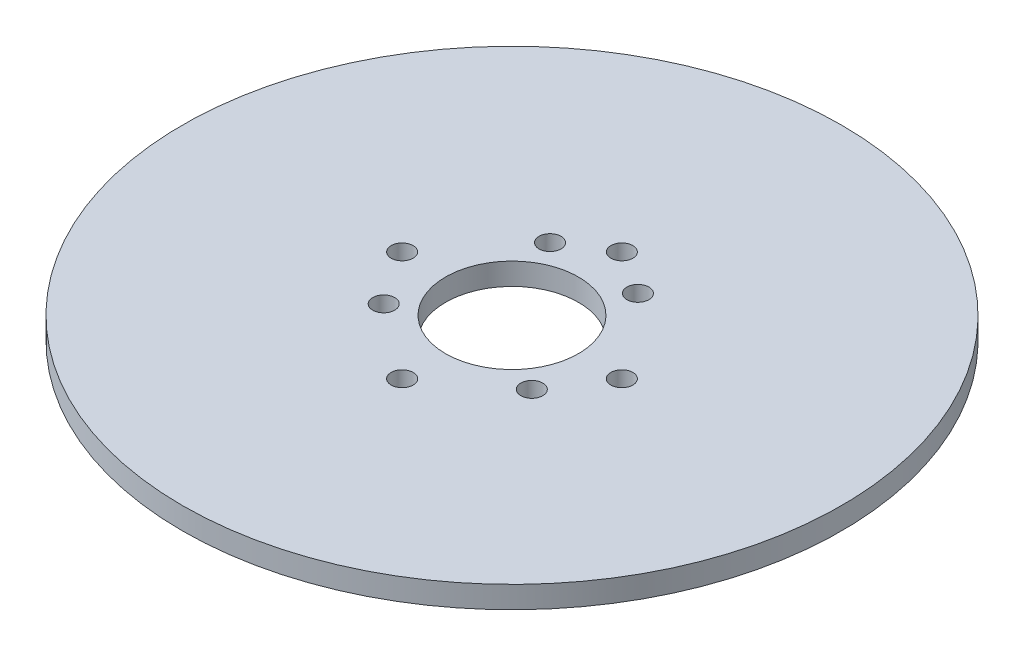
SolidWorks part; units mm, degrees
ref_plane "Front Plane" through (0, 0, 0) normal (0, 0, 1) x (1, 0, 0)
ref_plane "Top Plane" through (0, 0, 0) normal (0, 1, 0) x (1, 0, 0)
ref_plane "Right Plane" through (0, 0, 0) normal (1, 0, 0) x (0, 0, -1)
sketch "Sketch1" plane through (0, 0, 0) normal (0, 1, 0) x (1, 0, 0)
  line L0 (-20, 40.3113) -> (-33.7, -21.6932) construction
  line L1 (20, 40.3113) -> (33.7, -21.6932) construction
  line L2 (-20, 40.3113) -> (33.7, -21.6932) construction
  line L3 (20, 40.3113) -> (-33.7, -21.6932) construction
  line L4 (-20, 40.3113) -> (20, 40.3113) construction
  line L5 (-20, 40.3113) -> (0, 0) construction
  circle A0 centre (-20, 40.3113) radius 5
  circle A1 centre (20, 40.3113) radius 5
  circle A3 centre (33.7, -21.6932) radius 5
  circle A4 centre (-33.7, -21.6932) radius 5
  arc A10 (22.9505, 23.6727) -> (23.6461, 23.8093) centre (20.4099, 38.456) ccw
  circle A11 centre (0, 3) radius 30.25
  circle A12 centre (0, 53) radius 5
  circle A13 centre (50, 3) radius 5
  circle A14 centre (0, -47) radius 5
  circle A15 centre (-50, 3) radius 5
  circle A16 centre (0, 3) radius 150
  point P2 (0, 40.3113)
  point P17 (-33.7, -21.6932)
  point P18 (0, 0)
  point P25 (0, 3)
  point P26 (0, 0)
  dimension "D4" = 10
  dimension "D1" = 63.5
  dimension "D6" = 3
  dimension "D7" = 50
  dimension "D8" = 10
  dimension "D9" = 4
  dimension "D10" = 300
  dimension "D11" = 60.5
  dimension "D2" = 40
  dimension "D5" = 67.4
extrude "Boss-Extrude1" add sketch "Sketch1" along normal blind 10
